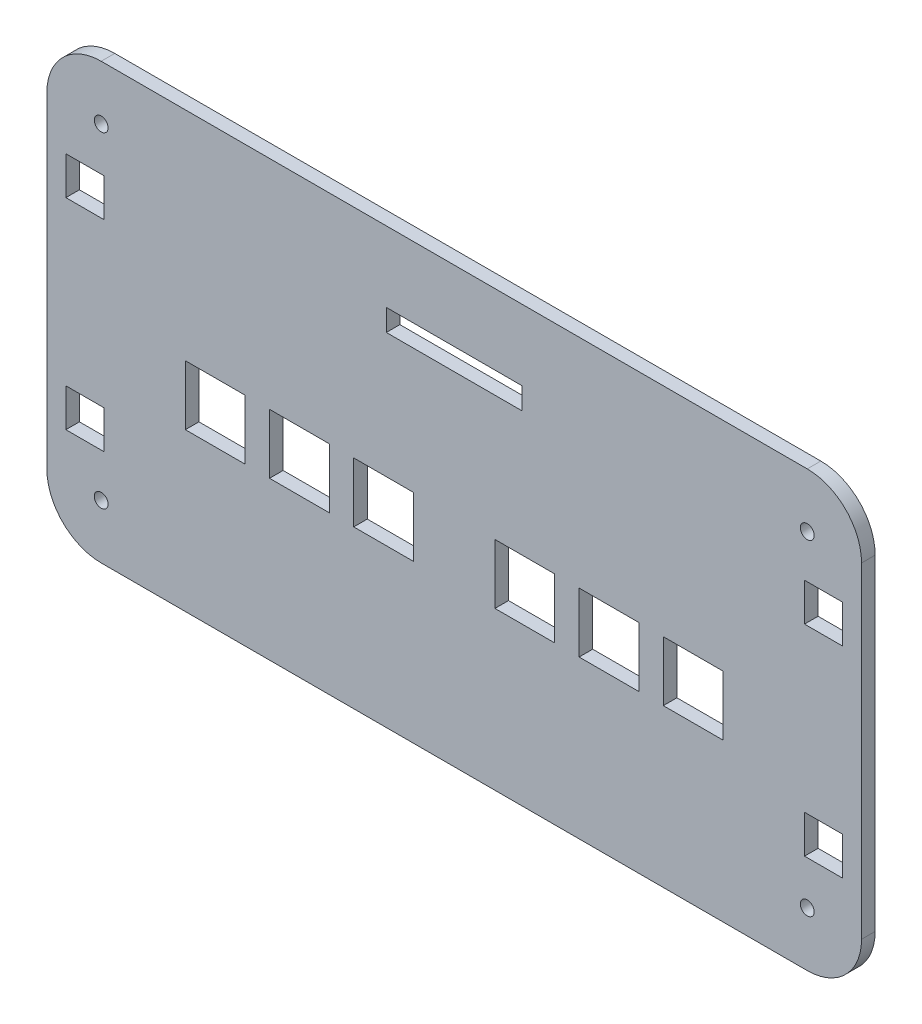
SolidWorks part; units mm, degrees
material "PMMA"
ref_plane "前视基准面" through (0, 0, 0) normal (0, 0, 1) x (1, 0, 0)
ref_plane "上视基准面" through (0, 0, 0) normal (0, 1, 0) x (1, 0, 0)
ref_plane "右视基准面" through (0, 0, 0) normal (1, 0, 0) x (0, 0, -1)
sketch "草图2" plane through (0, 0, 0) normal (0, 0, 1) x (1, 0, 0)
  line L0 (0, 1004.6496) -> (0, 4) construction
  line L6 (-37, -50) -> (-15, -50)
  line L7 (-37, -50) -> (-37, -72)
  line L8 (-37, -72) -> (-15, -72)
  line L9 (-15, -50) -> (-15, -72)
  line L10 (-37, -50) -> (-15, -72) construction
  line L11 (-37, -72) -> (-15, -50) construction
  line L19 (-22.1829, -50) -> (7.7078, -50) construction
  line L24 (-41.5, -57.5829) -> (-41.5, -62.5896) construction
  line L25 (-46, -72) -> (-68, -72)
  line L26 (-68, -50) -> (-68, -72)
  line L27 (-46, -50) -> (-68, -50)
  line L28 (-46, -50) -> (-46, -72)
  line L29 (-72.5, -57.5829) -> (-72.5, -71.3197) construction
  line L30 (-99, -50) -> (-99, -72)
  line L31 (-99, -50) -> (-77, -50)
  line L32 (-77, -50) -> (-77, -72)
  line L33 (-99, -72) -> (-77, -72)
  line L34 (37, -72) -> (15, -72)
  line L35 (15, -50) -> (15, -72)
  line L36 (37, -50) -> (15, -50)
  line L37 (37, -50) -> (37, -72)
  line L38 (46, -50) -> (46, -72)
  line L39 (46, -50) -> (68, -50)
  line L40 (68, -50) -> (68, -72)
  line L41 (46, -72) -> (68, -72)
  line L42 (99, -50) -> (77, -50)
  line L43 (77, -50) -> (77, -72)
  line L44 (99, -72) -> (77, -72)
  line L45 (99, -50) -> (99, -72)
  line L46 (129, -80) -> (143, -80)
  line L47 (-130, -130) -> (130, -130)
  line L48 (-150, -110) -> (-150, 10)
  line L49 (-130, 30) -> (130, 30)
  line L50 (150, -110) -> (150, 10)
  line L51 (0, 30) -> (0, 4) construction
  line L52 (-150, -50) -> (150, -50) construction
  line L53 (129, -6) -> (143, -6)
  line L58 (129, -6) -> (129, -20)
  line L59 (129, -20) -> (143, -20)
  line L60 (143, -6) -> (143, -20)
  line L65 (28.2222, 0) -> (37.5982, 0) construction
  line L66 (0, 0) -> (0, -130) construction
  line L67 (25, -4) -> (-25, -4)
  line L68 (25, -4) -> (25, 4)
  line L69 (25, 4) -> (-25, 4)
  line L70 (-25, -4) -> (-25, 4)
  line L71 (0, 0) -> (0, -4) construction
  line L72 (25, 0) -> (-25, 0) construction
  line L73 (0, 0) -> (0, -1009.2088) construction
  line L74 (136, -20) -> (136, -6) construction
  line L75 (129, -13) -> (143, -13) construction
  line L76 (143, -94) -> (143, -80)
  line L77 (129, -94) -> (143, -94)
  line L78 (129, -94) -> (129, -80)
  line L79 (-129, -94) -> (-129, -80)
  line L80 (-129, -94) -> (-143, -94)
  line L81 (-143, -94) -> (-143, -80)
  line L82 (-129, -80) -> (-143, -80)
  line L83 (-129, -20) -> (-143, -20)
  line L84 (-143, -6) -> (-143, -20)
  line L85 (-129, -6) -> (-143, -6)
  line L86 (-129, -6) -> (-129, -20)
  arc A0 (130, 30) -> (150, 10) centre (130, 10) cw
  arc A1 (150, -110) -> (130, -130) centre (130, -110) cw
  arc A2 (-130, -130) -> (-150, -110) centre (-130, -110) cw
  arc A3 (-150, 10) -> (-130, 30) centre (-130, 10) cw
  circle A5 centre (130, -110) radius 2.55
  circle A6 centre (130, 10) radius 2.55
  circle A7 centre (-130, -110) radius 2.55
  circle A8 centre (-130, 10) radius 2.55
  point P0 (0, 0)
  point P1 (0, 0)
  point P4 (-26, -61)
  point P38 (0, -50)
  point P40 (0, -50)
  point P41 (136, -13)
  point P61 (150, 30)
  point P64 (150, -130)
  point P70 (-150, 30)
  dimension "D15" = 20
  dimension "D16" = 5.1
  dimension "D17" = 5.1
  dimension "D18" = 5.1
  dimension "D19" = 5.1
  dimension "D20" = 30
  dimension "D3" = 22
  dimension "D4" = 22
  dimension "D5" = 15
  dimension "D6" = 50
  dimension "D7" = 8
  dimension "D8" = 4.5
  dimension "D9" = 4.5
  dimension "D10" = 300
  dimension "D11" = 160
  dimension "D12" = 14
  dimension "D13" = 14
  dimension "D14" = 7
  dimension "D22" = 50
extrude "凸台-拉伸1" add sketch "草图2" along normal blind 5
